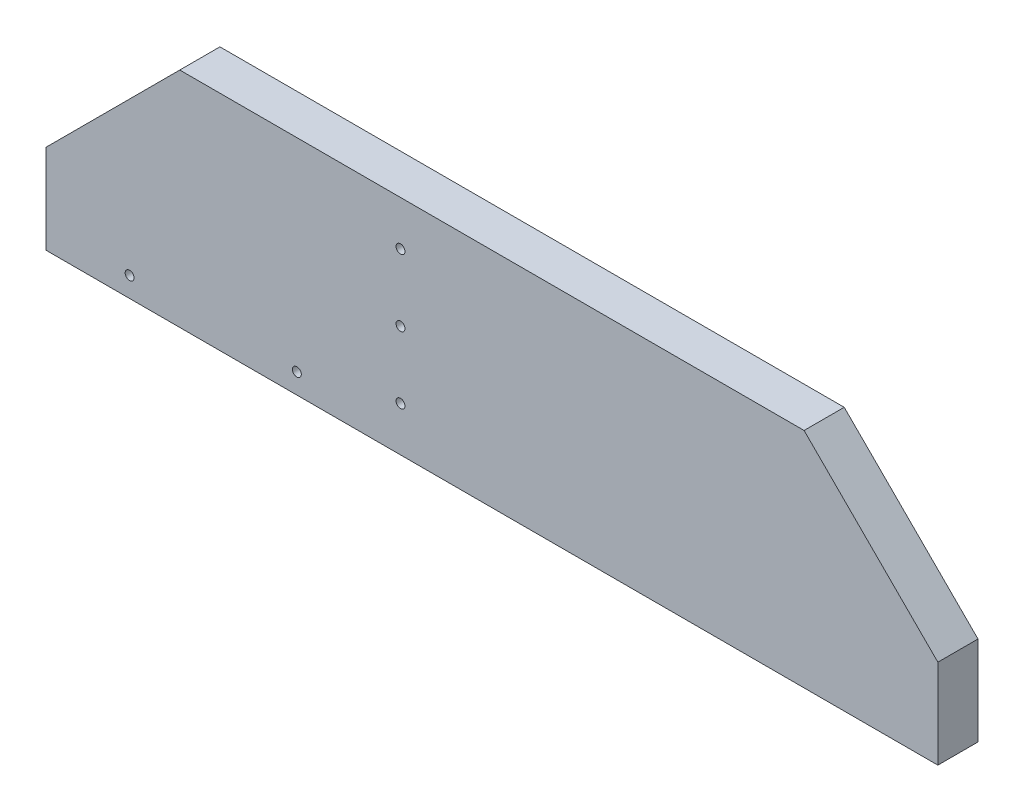
SolidWorks part; units mm, degrees
ref_plane "Plano frontal" through (0, 0, 0) normal (0, 0, 1) x (1, 0, 0)
ref_plane "Plano superior" through (0, 0, 0) normal (0, 1, 0) x (1, 0, 0)
ref_plane "Plano direito" through (0, 0, 0) normal (1, 0, 0) x (0, 0, -1)
sketch "Esboço1" plane through (0, 0, 0) normal (0, 0, 1) x (1, 0, 0)
  line L1 (-57.62, 25.4898) -> (-17.62, 25.4898)
  line L2 (-57.62, 25.4898) -> (-57.62, 15.4898)
  line L3 (-57.62, 15.4898) -> (-17.62, 15.4898)
  line L4 (-17.62, 25.4898) -> (-17.62, 15.4898)
extrude "Ressalto-extrusão1" add sketch "Esboço1" along normal blind 1.8
sketch "Esboço3" plane through (0, 0, 1.8) normal (0, 0, 1) x (1, 0, 0)
  line L0 (-51.62, 25.4898) -> (-57.62, 19.4898)
  line L1 (-17.62, 19.4898) -> (-23.62, 25.4898)
  line L2 (-57.62, 19.4898) -> (-57.62, 25.4898)
  line L3 (-17.62, 25.4898) -> (-57.62, 25.4898) construction
  line L4 (-57.62, 25.4898) -> (-57.62, 15.4898) construction
  line L5 (-57.62, 25.4898) -> (-51.62, 25.4898)
  line L6 (-23.62, 25.4898) -> (-17.62, 25.4898)
  line L7 (-17.62, 25.4898) -> (-17.62, 19.4898)
extrude "Corte-extrusão1" cut sketch "Esboço3" against normal blind 1.8
sketch "Esboço4" plane through (0, 0, 1.8) normal (0, 0, 1) x (1, 0, 0)
  line L0 (-42.62, 15.4898) -> (-40.82, 15.4898) construction
  line L1 (-41.72, 15.4898) -> (-41.72, 17.4898) construction
  line L2 (-41.72, 25.4898) -> (-41.72, 23.4898) construction
  line L3 (-23.62, 25.4898) -> (-51.62, 25.4898) construction
  line L4 (-42.62, 145.4898) -> (-42.62, 15.4898)
  line L5 (-42.62, 15.4898) -> (-40.82, 15.4898)
  line L6 (-40.82, 15.4898) -> (-40.82, 145.4898)
  line L7 (-40.82, 145.4898) -> (-42.62, 145.4898)
  line L9 (-42.62, 15.4898) -> (-40.82, 15.4898)
  line L11 (-40.82, 145.4898) -> (-42.62, 145.4898)
  line L12 (-41.72, 17.4898) -> (-41.72, 20.6898) construction
  line L13 (-41.72, 23.2898) -> (-41.72, 23.4898) construction
  circle A0 centre (-41.72, 17.4898) radius 0.2
  circle A1 centre (-41.72, 20.4898) radius 0.2
  circle A2 centre (-41.72, 23.4898) radius 0.2
  dimension "D2" = 2
  dimension "D4" = 0.4
  dimension "D3" = 2
  dimension "D1" = 0
extrude "Corte-extrusão2" cut sketch "Esboço4" against normal blind 1.8 contours A1 | A0 | A2
sketch "Esboço5" plane through (0, 0, 1.8) normal (0, 0, 1) x (1, 0, 0)
  line L1 (-53.87, 17.2898) -> (-53.87, 15.4898) construction
  line L2 (-57.62, 17.2898) -> (-50.12, 17.2898) construction
  line L3 (-50.12, 17.2898) -> (-42.62, 17.2898) construction
  line L4 (-57.62, 15.4898) -> (-17.62, 15.4898) construction
  line L5 (-46.37, 17.2898) -> (-46.37, 15.4898) construction
  circle A0 centre (-53.87, 16.3898) radius 0.2
  circle A1 centre (-46.37, 16.3898) radius 0.2
  point P13 (-46.37, 16.3898)
  point P14 (0, 0)
  dimension "D1" = 0.4
extrude "Corte-extrusão3" cut sketch "Esboço5" against normal through all
